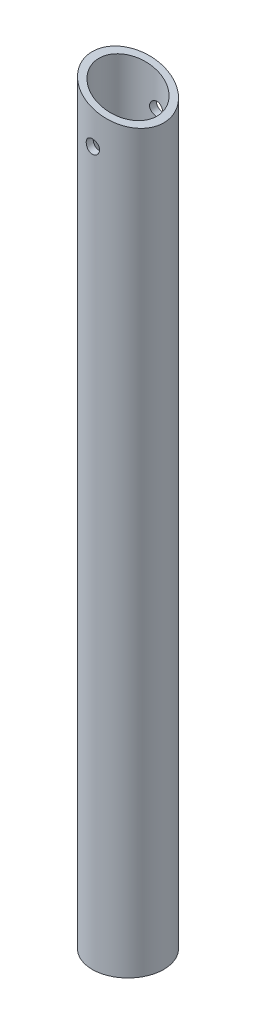
SolidWorks part; units mm, degrees
material "Thornel Mat VMA"
ref_plane "Ön Düzlem" through (0, 0, 0) normal (0, 0, 1) x (1, 0, 0)
ref_plane "Üst Düzlem" through (0, 0, 0) normal (0, 1, 0) x (1, 0, 0)
ref_plane "Sağ Düzlem" through (0, 0, 0) normal (1, 0, 0) x (0, 0, -1)
sketch "Çizim1" plane through (0, 0, 0) normal (0, 1, 0) x (1, 0, 0)
  circle A0 centre (0, 0) radius 8
  circle A1 centre (0, 0) radius 6.5
  dimension "D1" = 16
  dimension "D2" = 13
extrude "Yükseklik-Ekstrüzyon1" add sketch "Çizim1" along normal blind 170
sketch "Çizim3" plane through (0, 0, 0) normal (0, 0, 1) x (1, 0, 0)
  line L1 (0, 170) -> (0, 159.5882) construction
  line L2 (6.5, 170) -> (-6.5, 170) construction
  line L3 (-8, 170) -> (8, 164.1765)
  line L4 (8, 0) -> (8, 170) construction
  line L5 (8, 164.1765) -> (8, 170)
  line L6 (8, 170) -> (-8, 170)
  circle A0 centre (0, 159.5882) radius 1.5
  point P2 (0, 167.0882)
  dimension "D2" = 3
  dimension "D1" = 7.5
  dimension "D3" = 20
extrude "Kes-Ekstrüzyon1" cut sketch "Çizim3" against normal mid plane 20
